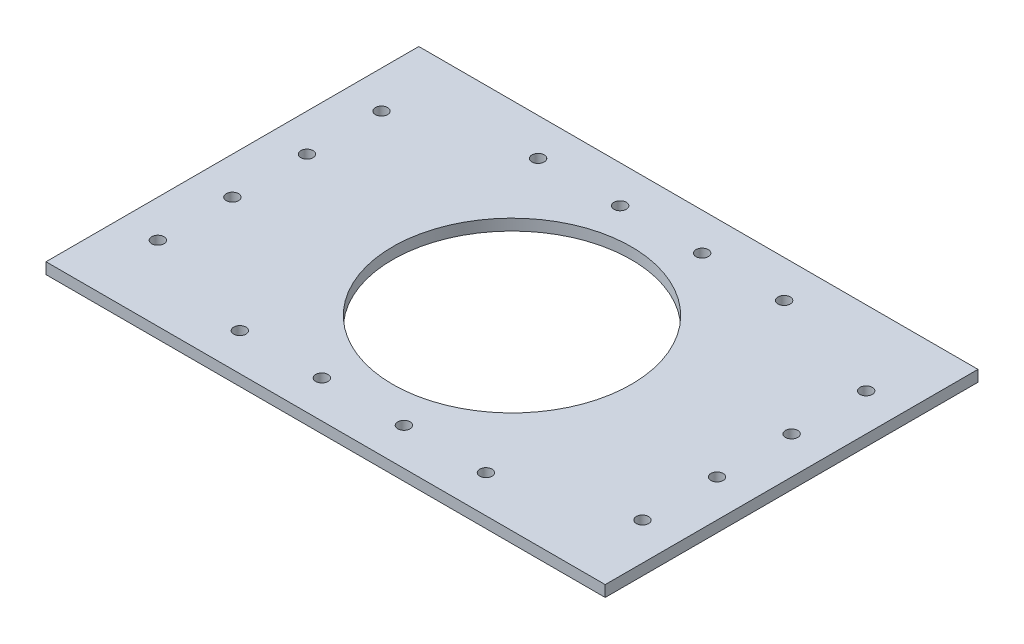
SolidWorks part; units mm, degrees
ref_plane "前视基准面" through (0, 0, 0) normal (0, 0, 1) x (1, 0, 0)
ref_plane "上视基准面" through (0, 0, 0) normal (0, 1, 0) x (1, 0, 0)
ref_plane "右视基准面" through (0, 0, 0) normal (1, 0, 0) x (0, 0, -1)
other "Configuration Table"
sketch "草图1" plane through (0, 0, 0) normal (0, 1, 0) x (1, 0, 0)
  line L0 (0, 0) -> (0, 77.0107) construction
  line L1 (-75, 50) -> (75, 50)
  line L2 (-75, 50) -> (-75, -50)
  line L3 (-75, -50) -> (75, -50)
  line L4 (75, 50) -> (75, -50)
  line L5 (-55, 0) -> (55, 0) construction
  line L6 (-75, -50) -> (75, 50) construction
  circle A0 centre (0, 0) radius 32
  circle A1 centre (-65, 30) radius 1.65
  circle A2 centre (-65, 10) radius 1.65
  circle A3 centre (-65, -10) radius 1.65
  circle A4 centre (-65, -30) radius 1.65
  circle A5 centre (65, -30) radius 1.65
  circle A6 centre (65, -10) radius 1.65
  circle A7 centre (65, 10) radius 1.65
  circle A8 centre (65, 30) radius 1.65
  circle A9 centre (33, 40) radius 1.65
  circle A13 centre (11, 40) radius 1.65
  circle A14 centre (-11, 40) radius 1.65
  circle A15 centre (-33, 40) radius 1.65
  circle A16 centre (33, -40) radius 1.65
  circle A17 centre (11, -40) radius 1.65
  circle A18 centre (-11, -40) radius 1.65
  circle A19 centre (-33, -40) radius 1.65
  point P0 (0, 0)
  dimension "D1" = 64
  dimension "D5" = 20
  dimension "D7" = 3.3
  dimension "D9" = 3.3
  dimension "D11" = 4
  dimension "D2" = 100
  dimension "D3" = 150
  dimension "D4" = 10
  dimension "D8" = 42
  dimension "D10" = 10
  dimension "D6" = 4
extrude "凸台-拉伸1" add sketch "草图1" along normal blind 3
